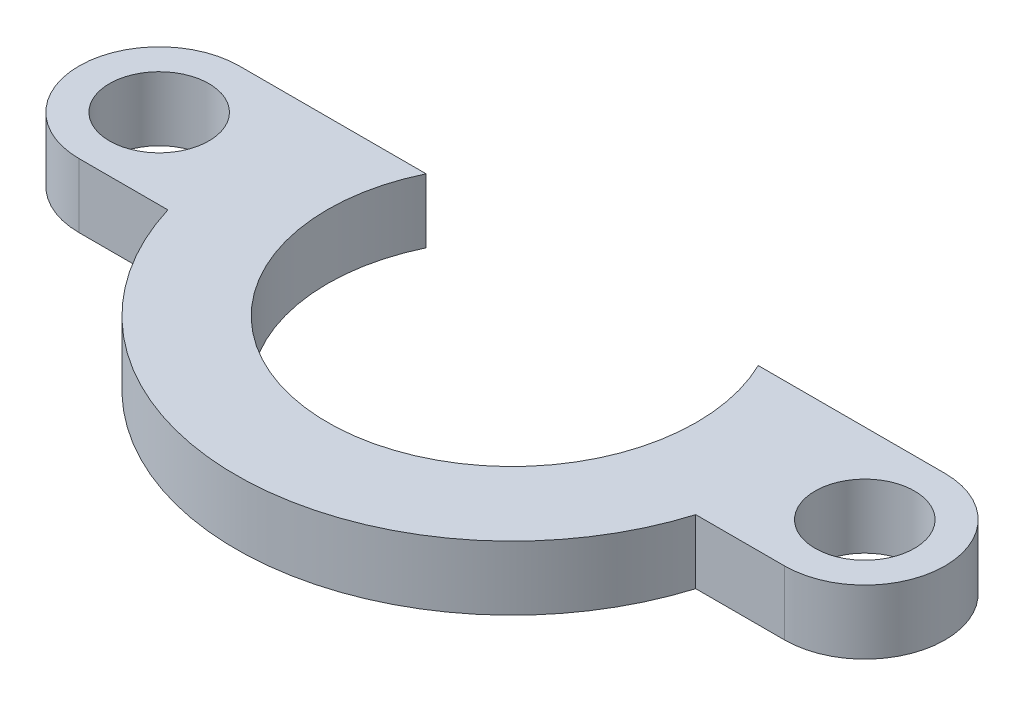
SolidWorks part; units mm, degrees
ref_plane "Front Plane" through (0, 0, 0) normal (0, 0, 1) x (1, 0, 0)
ref_plane "Top Plane" through (0, 0, 0) normal (0, 1, 0) x (1, 0, 0)
ref_plane "Right Plane" through (0, 0, 0) normal (1, 0, 0) x (0, 0, -1)
sketch "Sketch1" plane through (0, 0, 0) normal (0, 1, 0) x (1, 0, 0)
  line L0 (-11, 0) -> (11, 0) construction
  line L49 (-11, 2.5) -> (11, 2.5)
  line L50 (-11, 2.5) -> (-11, -2.5)
  line L57 (-11, -2.5) -> (11, -2.5)
  line L58 (11, 2.5) -> (11, -2.5)
  circle A22 centre (0, 0) radius 8.6
  circle A23 centre (0, 0) radius 5.75
  circle A24 centre (-11, 0) radius 1.55
  circle A25 centre (11, 0) radius 1.55
  circle A30 centre (-11, 0) radius 2.5
  circle A31 centre (11, 0) radius 2.5
  point P6 (-11.1393, 3.5049)
  point P7 (0, 0)
  point P8 (0, 0)
  point P9 (11, -3.1566)
  point P59 (0, 0)
  dimension "D3" = 5
  dimension "D4" = 5
  dimension "D18" = 11.5
  dimension "D19" = 17.2
  dimension "D20" = 3.1
  dimension "D21" = 3.1
  dimension "D22" = 22
extrude "Boss-Extrude1" add sketch "Sketch1" along normal blind 2 contours A23 L57 A22 | L0 A30 A22 L57 A23 | A30 L0 A23 L49 A22 | A30 A22 L49 | A30 L57 A22 | A22 L0 A30 | L0 A22 A30 | L0 A23 L57 A22 A31 | A23 L0 A31 A22 L49 | A31 L49 A22 | A31 A22 L57 | L0 A22 A31 L58 A25 | A22 L0 A25 L58 A31 | A31 L0 A22 | L0 A31 A22 | L58 A31 A25 | A24
